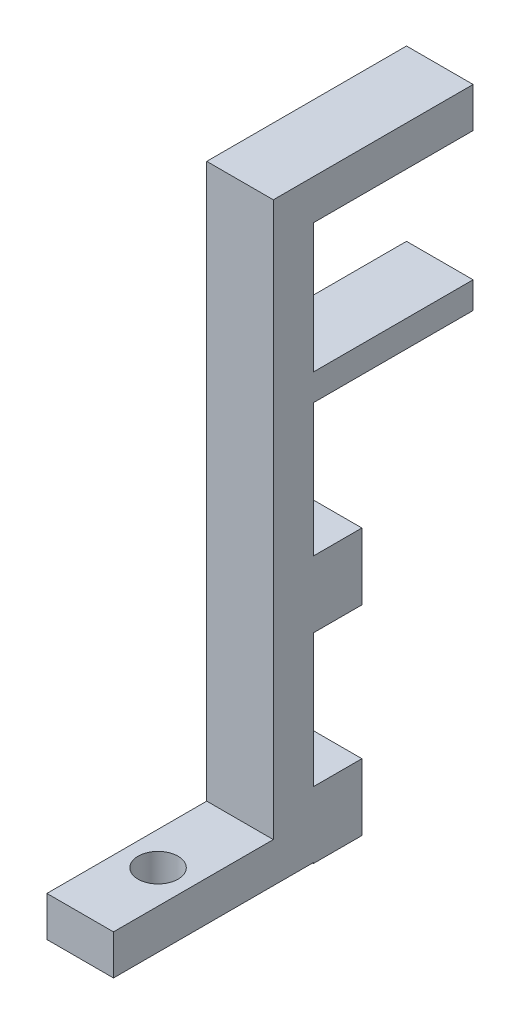
SolidWorks part; units mm, degrees
ref_plane "Front Plane" through (0, 0, 0) normal (0, 0, 1) x (1, 0, 0)
ref_plane "Top Plane" through (0, 0, 0) normal (0, 1, 0) x (1, 0, 0)
ref_plane "Right Plane" through (0, 0, 0) normal (1, 0, 0) x (0, 0, -1)
sketch "Sketch1" plane through (0, 0, 0) normal (0, 0, 1) x (1, 0, 0)
  line L1 (2.5, -19.3) -> (-2.5, -19.3)
  line L2 (2.5, -19.3) -> (2.5, 19.3)
  line L3 (2.5, 19.3) -> (-2.5, 19.3)
  line L4 (-2.5, -19.3) -> (-2.5, 19.3)
  line L5 (2.5, -19.3) -> (-2.5, 19.3) construction
  line L6 (2.5, 19.3) -> (-2.5, -19.3) construction
  point P0 (0, 0)
  dimension "D1" = 38.6
  dimension "D2" = 5
extrude "Boss-Extrude1" add sketch "Sketch1" along normal blind 3
sketch "Sketch3" plane through (0, -19.3, 0) normal (0, -1, 0) x (1, 0, 0)
  line L1 (-2.5, 0) -> (2.5, 0)
  line L2 (-2.5, 0) -> (-2.5, 15)
  line L3 (-2.5, 15) -> (2.5, 15)
  line L4 (2.5, 0) -> (2.5, 15)
  dimension "D1" = 15
  dimension "D2" = 5
extrude "Boss-Extrude2" add sketch "Sketch3" along normal blind 3
sketch "Sketch4" plane through (0, -19.3, 0) normal (0, 1, 0) x (1, 0, 0)
  circle A0 centre (0, -9.1532) radius 1.5
extrude "Cut-Extrude1" cut sketch "Sketch4" against normal blind 4
sketch "Sketch7" plane through (0, 19.3, 0) normal (0, 1, 0) x (1, 0, 0)
  line L1 (-2.5, -3) -> (2.5, -3)
  line L2 (-2.5, -3) -> (-2.5, 12)
  line L3 (-2.5, 12) -> (2.5, 12)
  line L4 (2.5, -3) -> (2.5, 12)
  dimension "D1" = 15
  dimension "D2" = 5
extrude "Boss-Extrude3" add sketch "Sketch7" along normal blind 3
sketch "Sketch8" plane through (0, 0, 0) normal (0, 0, -1) x (-1, 0, 0)
  line L0 (2.5, 19.3) -> (2.5, -22.3) construction
  line L1 (2.5, 7.6) -> (-2.5, 7.6)
  line L2 (2.5, 7.6) -> (2.5, 9.6)
  line L3 (2.5, 9.6) -> (-2.5, 9.6)
  line L4 (-2.5, 7.6) -> (-2.5, 9.6)
  line L5 (-2.5, -22.3) -> (-2.5, 19.3) construction
  line L7 (-2.5, 19.3) -> (2.5, 19.3) construction
  dimension "D1" = 9.7
  dimension "D2" = 2
extrude "Boss-Extrude4" add sketch "Sketch8" along normal blind 12
sketch "Sketch10" plane through (0, 0, 0) normal (0, 0, -1) x (-1, 0, 0)
  line L0 (-2.5, -22.3) -> (-2.5, 7.6) construction
  line L1 (-2.5, -2.3643) -> (2.5, -2.3643)
  line L2 (-2.5, -2.3643) -> (-2.5, -7.3643)
  line L3 (-2.5, -7.3643) -> (2.5, -7.3643)
  line L4 (2.5, -2.3643) -> (2.5, -7.3643)
  line L5 (2.5, 7.6) -> (2.5, -22.3) construction
  line L8 (-2.5, -17.3643) -> (2.5, -17.3643)
  line L9 (-2.5, -17.3643) -> (-2.5, -22.3643)
  line L10 (-2.5, -22.3643) -> (2.5, -22.3643)
  line L11 (2.5, -17.3643) -> (2.5, -22.3643)
  dimension "D1" = 5
  dimension "D2" = 10
  dimension "D4" = 5
extrude "Boss-Extrude5" add sketch "Sketch10" along normal blind 3.65
